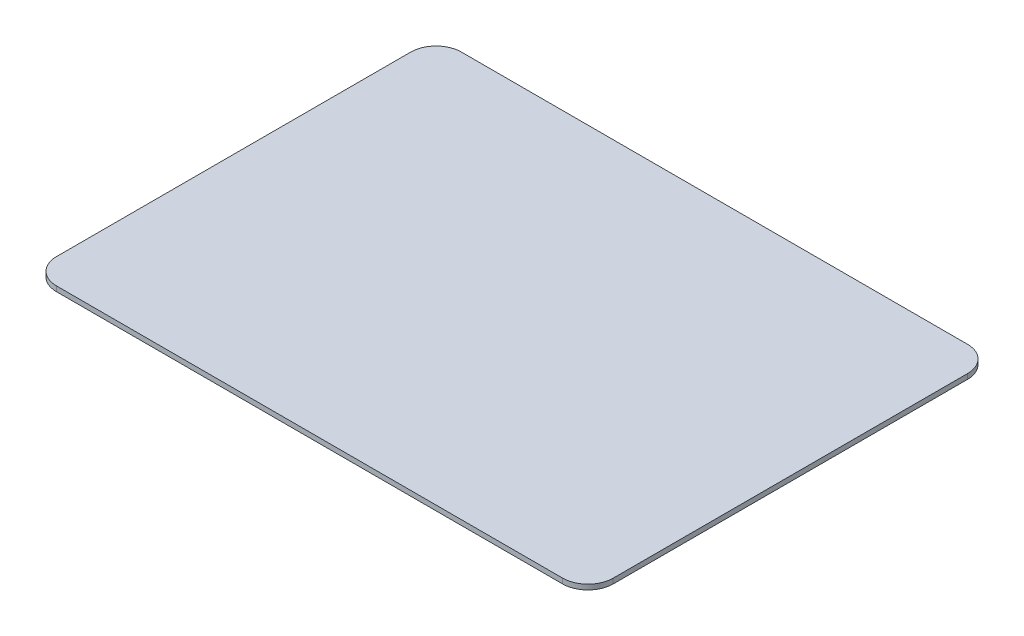
SolidWorks part; units mm, degrees
ref_plane "Front Plane" through (0, 0, 0) normal (0, 0, 1) x (1, 0, 0)
ref_plane "Top Plane" through (0, 0, 0) normal (0, 1, 0) x (1, 0, 0)
ref_plane "Right Plane" through (0, 0, 0) normal (1, 0, 0) x (0, 0, -1)
sketch "Sketch1" plane through (0, 0, 0) normal (0, 1, 0) x (1, 0, 0)
  line L1 (-127, -101.6) -> (127, -101.6)
  line L2 (-139.7, -88.9) -> (-139.7, 88.9)
  line L3 (-127, 101.6) -> (127, 101.6)
  line L4 (139.7, -88.9) -> (139.7, 88.9)
  line L5 (-139.7, -101.6) -> (139.7, 101.6) construction
  line L6 (-139.7, 101.6) -> (139.7, -101.6) construction
  arc A0 (139.7, 88.9) -> (127, 101.6) centre (127, 88.9) ccw
  arc A1 (127, -101.6) -> (139.7, -88.9) centre (127, -88.9) ccw
  arc A2 (-139.7, -88.9) -> (-127, -101.6) centre (-127, -88.9) ccw
  arc A3 (-139.7, 88.9) -> (-127, 101.6) centre (-127, 88.9) cw
  point P0 (0, 0)
  dimension "D3" = 12.7
  dimension "D1" = 279.4
  dimension "D2" = 203.2
extrude "Boss-Extrude1" add sketch "Sketch1" along normal blind 2.54
